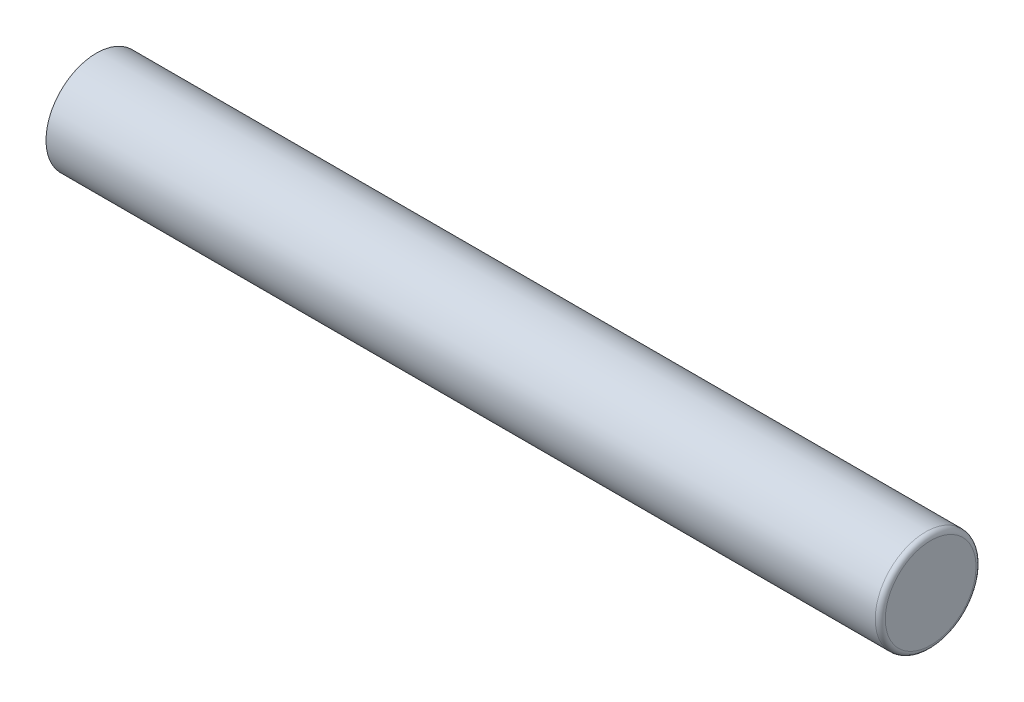
SolidWorks part; units mm, degrees
material "AISI 316 Barra de acero inoxidable recocido (SS)"
ref_plane "Alzado" through (0, 0, 0) normal (0, 0, 1) x (1, 0, 0)
ref_plane "Planta" through (0, 0, 0) normal (0, 1, 0) x (1, 0, 0)
ref_plane "Vista lateral" through (0, 0, 0) normal (1, 0, 0) x (0, 0, -1)
sketch "Croquis1" plane through (0, 0, 0) normal (0, 0, 1) x (1, 0, 0)
  line L1 (0, 0) -> (41.4, 0)
  line L2 (0, 0) -> (0, 2.5)
  line L3 (0, 2.5) -> (41.4, 2.5)
  line L4 (41.4, 0) -> (41.4, 2.5)
  dimension "D1" = 2.5
  dimension "D2" = 41.4
revolve "Revolución1" add sketch "Croquis1" angle 360 about L1
fillet "Redondeo1" radius 0.25 1 edges at (41.4, 0, 2.5)
